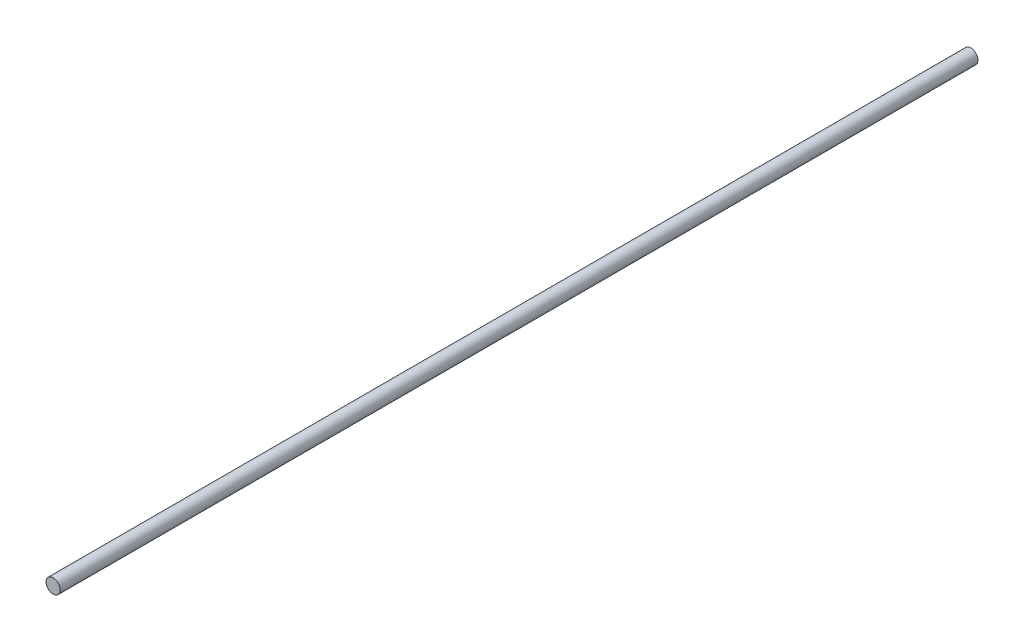
SolidWorks part; units mm, degrees
material "2024 Alloy"
ref_plane "Front Plane" through (0, 0, 0) normal (0, 0, 1) x (1, 0, 0)
ref_plane "Top Plane" through (0, 0, 0) normal (0, 1, 0) x (1, 0, 0)
ref_plane "Right Plane" through (0, 0, 0) normal (1, 0, 0) x (0, 0, -1)
sketch "Sketch1" plane through (0, 0, 0) normal (0, 0, 1) x (1, 0, 0)
  circle A0 centre (0, 0) radius 1.1811
  dimension "D1" = 2.3622
extrude "RodEnd" add sketch "Sketch1" against normal blind 152.4
